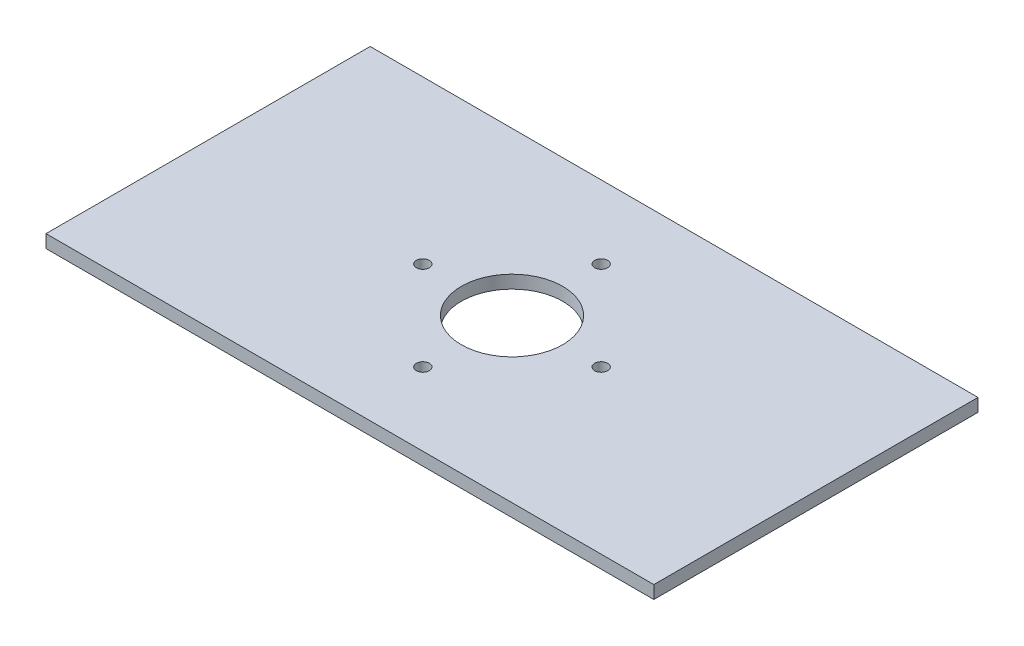
SolidWorks part; units mm, degrees
ref_plane "前视基准面" through (0, 0, 0) normal (0, 0, 1) x (1, 0, 0)
ref_plane "上视基准面" through (0, 0, 0) normal (0, 1, 0) x (1, 0, 0)
ref_plane "右视基准面" through (0, 0, 0) normal (1, 0, 0) x (0, 0, -1)
other "Configuration Table"
sketch "草图1" plane through (0, 0, 0) normal (0, 1, 0) x (1, 0, 0)
  line L0 (0, 40) -> (0, -40) construction
  line L1 (-75, 40) -> (75, 40)
  line L2 (-75, 40) -> (-75, -40)
  line L3 (-75, -40) -> (75, -40)
  line L4 (75, 40) -> (75, -40)
  line L6 (-75, 0) -> (75, 0) construction
  dimension "D1" = 80
  dimension "D2" = 150
extrude "凸台-拉伸1" add sketch "草图1" along normal blind 3.2
sketch "草图2" plane through (0, 3.2, 0) normal (0, 1, 0) x (1, 0, 0)
  circle A0 centre (0, 0) radius 12.5
  dimension "D1" = 25
extrude "切除-拉伸1" cut sketch "草图2" against normal up to surface (3.2 mm away) up to face at (0, 0, 0)
sketch "草图3" plane through (0, 3.2, 0) normal (0, 1, 0) x (1, 0, 0)
  line L0 (0, -1.5517) -> (0, 1.5517) construction
  circle A0 centre (0, -22) radius 1.6
  circle A1 centre (-22, 0) radius 1.6
  circle A2 centre (0, 22) radius 1.6
  circle A3 centre (22, 0) radius 1.6
  point P4 (16.2356, 8.952)
  point P5 (0, 0)
  point P14 (0, 0)
  point P15 (0, 0)
  point P16 (0, 0)
  point P17 (24.5109, 2.5109)
  point P18 (14.9741, -7.0259)
  point P19 (0, 0)
  dimension "D2" = 3.2
  dimension "D1" = 22
  dimension "D3" = 4
extrude "切除-拉伸3" cut sketch "草图3" against normal up to surface (3.2 mm away) contours A1 | A2 | A3 | A0 up to face at (0, 0, 12.5)
